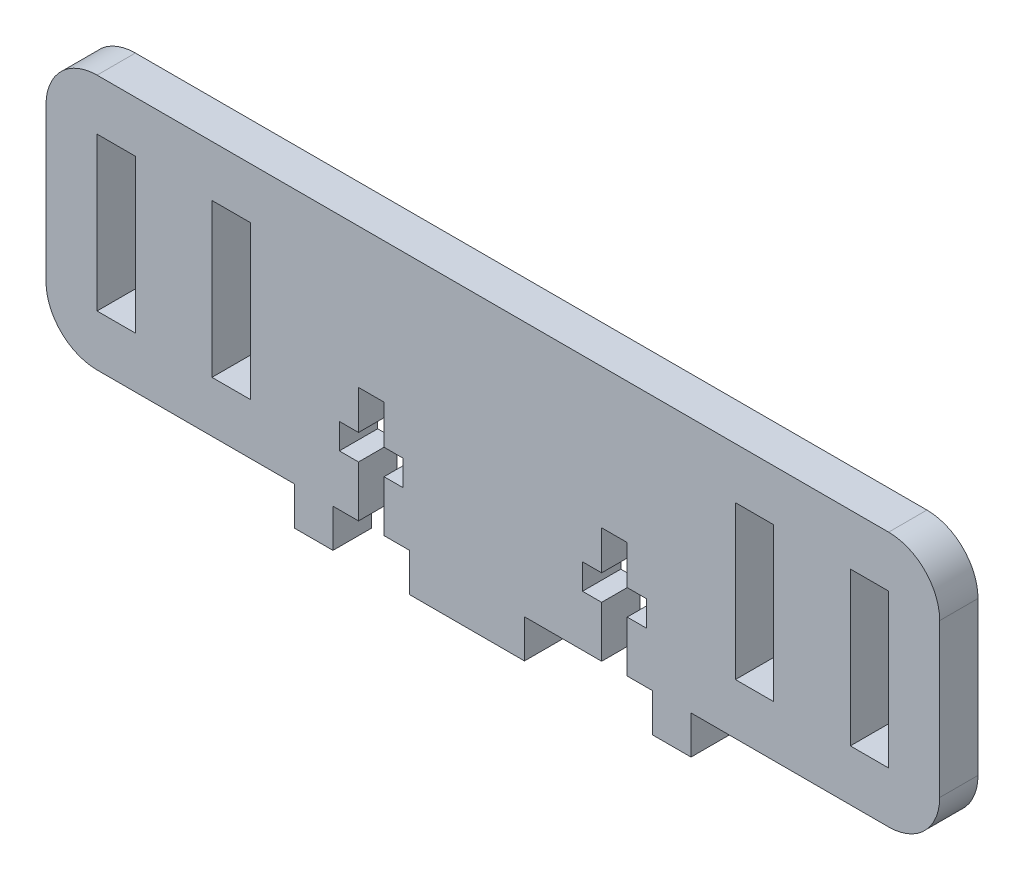
SolidWorks part; units mm, degrees
ref_plane "Plan de face" through (0, 0, 0) normal (0, 0, 1) x (1, 0, 0)
ref_plane "Plan de dessus" through (0, 0, 0) normal (0, 1, 0) x (1, 0, 0)
ref_plane "Plan de droite" through (0, 0, 0) normal (1, 0, 0) x (0, 0, -1)
sketch "Esquisse1" plane through (0, 0, 0) normal (0, 0, 1) x (1, 0, 0)
  line L0 (-175, 30) -> (175, 30) construction
  line L1 (-155, -50) -> (155, -50)
  line L2 (-175, -30) -> (-175, 30)
  line L3 (-155, 50) -> (155, 50)
  line L4 (175, -30) -> (175, 30)
  line L5 (-175, -50) -> (175, 50) construction
  line L6 (-175, 50) -> (175, -50) construction
  line L7 (175, -30) -> (-175, -30) construction
  line L8 (140, 30) -> (155, 30)
  line L9 (140, 30) -> (140, -30)
  line L10 (155, 30) -> (155, -30)
  line L11 (140, -30) -> (155, -30)
  line L12 (110, 30) -> (95, 30)
  line L13 (110, 30) -> (110, -30)
  line L14 (95, 30) -> (95, -30)
  line L15 (110, -30) -> (95, -30)
  line L16 (-155, 30) -> (-140, 30)
  line L17 (-155, 30) -> (-155, -30)
  line L18 (-140, 30) -> (-140, -30)
  line L19 (-155, -30) -> (-140, -30)
  line L20 (0, 50) -> (0, -50) construction
  line L21 (-60.11, -30) -> (-35.11, -30)
  line L22 (-60.11, -30) -> (-60.11, -20)
  line L23 (42.61, -45.2728) -> (52.61, -45.2728)
  line L24 (42.61, -45.2728) -> (42.61, -4.7141)
  line L25 (42.61, -4.7141) -> (52.61, -4.7141)
  line L26 (52.61, -45.2728) -> (52.61, -4.7141)
  line L27 (42.61, -45.2728) -> (52.61, -4.7141) construction
  line L28 (42.61, -4.7141) -> (52.61, -45.2728) construction
  line L29 (35.11, -30) -> (60.11, -30)
  line L30 (35.11, -30) -> (35.11, -20)
  line L31 (35.11, -20) -> (60.11, -20)
  line L32 (60.11, -30) -> (60.11, -20)
  line L33 (35.11, -30) -> (60.11, -20) construction
  line L34 (35.11, -20) -> (60.11, -30) construction
  line L35 (-35.11, -20) -> (-60.11, -20)
  line L36 (-35.11, -30) -> (-35.11, -20)
  line L37 (-42.61, -45.2728) -> (-52.61, -45.2728)
  line L38 (-42.61, -4.7141) -> (-52.61, -4.7141)
  line L39 (-42.61, -45.2728) -> (-42.61, -4.7141)
  line L40 (-52.61, -45.2728) -> (-52.61, -4.7141)
  line L41 (-77.61, -30) -> (77.61, -30)
  line L42 (47.61, -4.7141) -> (47.61, -45.2728) construction
  line L43 (47.61, -20) -> (47.61, -30) construction
  line L44 (-110, 30) -> (-95, 30)
  line L45 (-110, -30) -> (-95, -30)
  line L46 (-110, 30) -> (-110, -30)
  line L47 (-95, 30) -> (-95, -30)
  arc A0 (-175, 30) -> (-155, 50) centre (-155, 30) cw
  arc A1 (155, -50) -> (175, -30) centre (155, -30) ccw
  arc A2 (175, 30) -> (155, 50) centre (155, 30) ccw
  arc A3 (-155, -50) -> (-175, -30) centre (-155, -30) cw
  point P0 (0, 0)
  point P29 (49.9252, -24.9934)
  point P32 (0, -30)
  point P37 (47.61, -25)
  point P51 (0, -30)
  dimension "D3" = 20
  dimension "D4" = 20
  dimension "D1" = 350
  dimension "D2" = 100
  dimension "D5" = 15
  dimension "D6" = 15
  dimension "D7" = 30
  dimension "D8" = 15
  dimension "D9" = 155.22
  dimension "D10" = 25
  dimension "D11" = 10
  dimension "D12" = 25
  dimension "D13" = 10
extrude "Boss.-Extru.1" add sketch "Esquisse1" along normal blind 15 contours L29 L32 L31 L26 | L31 L30 L29 L24 | L9 L11 L10 L8 | L15 L13 L12 L14 | L47 L44 L46 L45 | L17 L19 L18 L16 | L3 A2 L4 A1 L1 A3 L2 A0 | L39 L38 L40 L37 | L35 L22 L21 L36
sketch "Esquisse2" plane through (0, 0, 15) normal (0, 0, 1) x (1, 0, 0)
  line L0 (42.61, -45.2728) -> (52.61, -45.2728)
  line L1 (42.61, -45.2728) -> (42.61, -53.9824)
  line L2 (52.61, -45.2728) -> (52.61, -53.9824)
  line L3 (42.61, -53.9824) -> (52.61, -53.9824)
  line L4 (-52.61, -45.2728) -> (-42.61, -45.2728)
  line L5 (-52.61, -45.2728) -> (-52.61, -57.1031)
  line L6 (-42.61, -45.2728) -> (-42.61, -57.1031)
  line L7 (-52.61, -57.1031) -> (-42.61, -57.1031)
extrude "Enlèv. mat.-Extru.1" cut sketch "Esquisse2" against normal through all
sketch "Esquisse3" plane through (0, -50, 0) normal (0, -1, 0) x (-1, 0, 0)
  line L0 (-62.61, -15) -> (-62.61, 0)
  line L1 (-62.61, -15) -> (-77.61, -15)
  line L2 (-62.61, 0) -> (-77.61, 0)
  line L3 (-77.61, -15) -> (-77.61, 0)
  line L4 (-52.61, -15) -> (-155, -15) construction
  line L5 (-52.61, 0) -> (-155, 0) construction
  line L6 (-52.61, -15) -> (-52.61, 0) construction
  line L7 (32.61, -15) -> (32.61, 0)
  line L8 (32.61, -15) -> (-12.39, -15)
  line L9 (32.61, 0) -> (-12.39, 0)
  line L10 (-12.39, -15) -> (-12.39, 0)
  line L11 (42.61, -15) -> (-42.61, -15) construction
  line L12 (42.61, 0) -> (-42.61, 0) construction
  line L13 (42.61, -15) -> (42.61, 0) construction
  line L14 (62.61, -15) -> (62.61, 0)
  line L15 (62.61, -15) -> (77.61, -15)
  line L16 (62.61, 0) -> (77.61, 0)
  line L17 (77.61, -15) -> (77.61, 0)
  line L18 (155, -15) -> (52.61, -15) construction
  line L19 (155, 0) -> (52.61, 0) construction
  line L20 (52.61, 0) -> (52.61, -15) construction
  dimension "D1" = 10
  dimension "D2" = 15
  dimension "D3" = 10
  dimension "D4" = 45
  dimension "D5" = 10
  dimension "D6" = 15
extrude "Boss.-Extru.2" add sketch "Esquisse3" along normal blind 15
